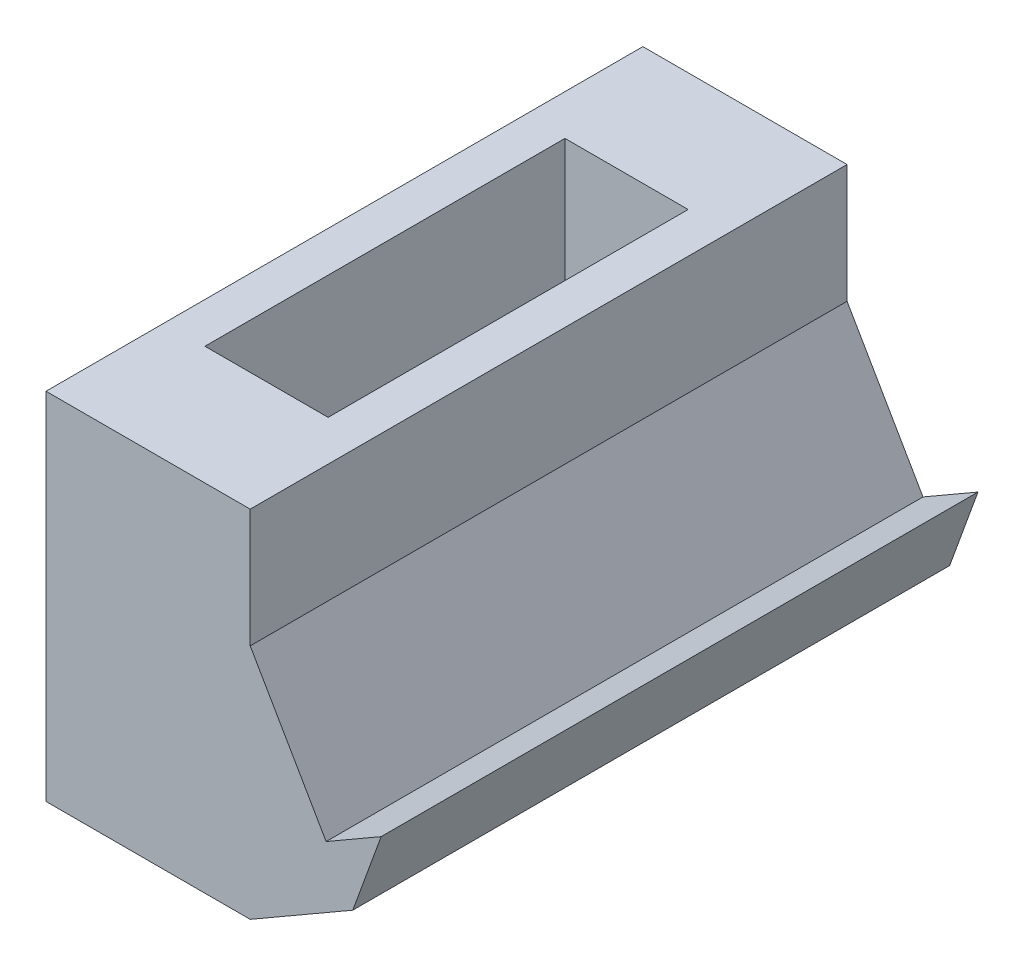
SolidWorks part; units mm, degrees
ref_plane "Front Plane" through (0, 0, 0) normal (0, 0, 1) x (1, 0, 0)
ref_plane "Top Plane" through (0, 0, 0) normal (0, 1, 0) x (1, 0, 0)
ref_plane "Right Plane" through (0, 0, 0) normal (1, 0, 0) x (0, 0, -1)
sketch "草图1" plane through (0, 0, 0) normal (0, 1, 0) x (1, 0, 0)
  line L1 (-4.3105, 12.6) -> (4.3105, 12.6)
  line L2 (-4.3105, 12.6) -> (-4.3105, -12.6)
  line L3 (-4.3105, -12.6) -> (4.3105, -12.6)
  line L4 (4.3105, 12.6) -> (4.3105, -12.6)
  line L5 (-4.3105, 12.6) -> (4.3105, -12.6) construction
  line L6 (-4.3105, -12.6) -> (4.3105, 12.6) construction
  line L7 (-2.6, 7.6) -> (2.6, 7.6)
  line L8 (-2.6, 7.6) -> (-2.6, -7.6)
  line L9 (-2.6, -7.6) -> (2.6, -7.6)
  line L10 (2.6, 7.6) -> (2.6, -7.6)
  line L11 (-2.6, 7.6) -> (2.6, -7.6) construction
  line L12 (-2.6, -7.6) -> (2.6, 7.6) construction
  point P0 (0, 0)
  point P6 (0, 0)
  dimension "D1" = 15.2
  dimension "D2" = 5.2
  dimension "D3" = 5
extrude "凸台-拉伸1" add sketch "草图1" along normal blind 5 and the other way blind 10
sketch "草图2" plane through (0, 0, 12.6) normal (0, 0, 1) x (1, 0, 0)
  line L0 (8.6407, -7.5) -> (9.8377, -4.2111)
  line L1 (4.3105, -10) -> (4.3105, 0)
  line L2 (4.3105, 0) -> (7.5158, -5.5517)
  line L3 (8.6407, -7.5) -> (4.3105, -10)
  line L4 (9.8377, -4.2111) -> (7.5158, -5.5517)
  dimension "D1" = 40
  dimension "D2" = 60
  dimension "D3" = 3.5
  dimension "D4" = 50
extrude "凸台-拉伸2" add sketch "草图2" against normal up to surface (25.2 mm away) up to face at (0, -2.5, -12.6)
